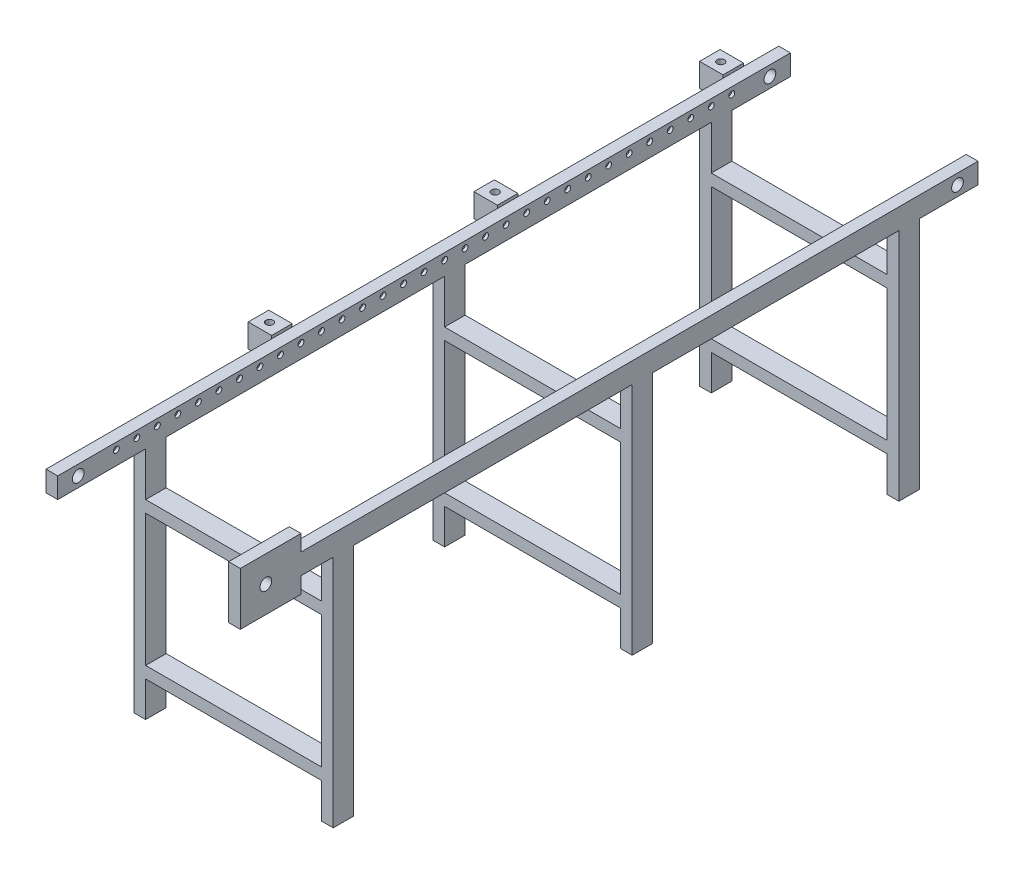
SolidWorks part; units mm, degrees
ref_plane "Front Plane" through (0, 0, 0) normal (0, 0, 1) x (1, 0, 0)
ref_plane "Top Plane" through (0, 0, 0) normal (0, 1, 0) x (1, 0, 0)
ref_plane "Right Plane" through (0, 0, 0) normal (1, 0, 0) x (0, 0, -1)
ref_plane "Plane1" through (300, 0, 0) normal (1, 0, 0) x (0, 0, -1)
sketch "Sketch3" plane through (300, 0, 0) normal (1, 0, 0) x (0, 0, -1)
  line L1 (-1250, 35) -> (1250, 35)
  line L2 (-1250, 35) -> (-1250, -35)
  line L3 (-1250, -35) -> (1250, -35)
  line L4 (1250, 35) -> (1250, -35)
  line L5 (-1250, 35) -> (1250, -35) construction
  line L6 (-1250, -35) -> (1250, 35) construction
  line L7 (-950, -35) -> (-880, -35)
  line L8 (-950, -35) -> (-950, -835)
  line L9 (-950, -835) -> (-880, -835)
  line L10 (-880, -35) -> (-880, -835)
  line L11 (70, -35) -> (140, -35)
  line L12 (70, -35) -> (70, -835)
  line L13 (70, -835) -> (140, -835)
  line L14 (140, -35) -> (140, -835)
  line L15 (980, -35) -> (1050, -35)
  line L16 (980, -35) -> (980, -835)
  line L17 (980, -835) -> (1050, -835)
  line L18 (1050, -35) -> (1050, -835)
  point P0 (0, 0)
  dimension "D1" = 2500
  dimension "D2" = 70
  dimension "D3" = 70
  dimension "D4" = 800
  dimension "D5" = 300
  dimension "D6" = 200
  dimension "D7" = 950
extrude "Boss-Extrude1" add sketch "Sketch3" along normal blind 40 contours L14 L3 L12 L13 | L4 L1 L2 L3 | L10 L3 L8 L9 | L18 L3 L16 L17
sketch "Sketch4" plane through (300, 0, 0) normal (-1, 0, 0) x (0, 0, 1)
  line L0 (-1050, -35) -> (-1050, -835) construction
  line L1 (-1050, -185) -> (-980, -185)
  line L2 (-1050, -185) -> (-1050, -225)
  line L3 (-1050, -225) -> (-980, -225)
  line L4 (-980, -185) -> (-980, -225)
  line L5 (-980, -35) -> (-980, -835) construction
  line L6 (-140, -35) -> (-140, -835) construction
  line L7 (-140, -185) -> (-70, -185)
  line L8 (-140, -185) -> (-140, -225)
  line L9 (-140, -225) -> (-70, -225)
  line L10 (-70, -185) -> (-70, -225)
  line L11 (-70, -35) -> (-70, -835) construction
  line L12 (880, -35) -> (880, -835) construction
  line L13 (880, -185) -> (950, -185)
  line L14 (880, -185) -> (880, -225)
  line L15 (880, -225) -> (950, -225)
  line L16 (950, -185) -> (950, -225)
  line L17 (950, -35) -> (950, -835) construction
  line L18 (-140, -35) -> (-980, -35) construction
  line L19 (-1050, -675) -> (-980, -675)
  line L20 (-1050, -675) -> (-1050, -715)
  line L21 (-1050, -715) -> (-980, -715)
  line L22 (-980, -675) -> (-980, -715)
  line L23 (-140, -675) -> (-70, -675)
  line L24 (-140, -675) -> (-140, -715)
  line L25 (-140, -715) -> (-70, -715)
  line L26 (-70, -675) -> (-70, -715)
  line L27 (880, -675) -> (950, -675)
  line L28 (880, -675) -> (880, -715)
  line L29 (880, -715) -> (950, -715)
  line L30 (950, -675) -> (950, -715)
  line L31 (-980, -835) -> (-1050, -835) construction
  dimension "D1" = 40
  dimension "D2" = 150
  dimension "D3" = 120
extrude "Boss-Extrude2" add sketch "Sketch4" along normal blind 300
mirror "Mirror2" about plane through (0, 0, 0) normal (1, 0, 0) of "Boss-Extrude1", "Boss-Extrude2"
mirror "Mirror3" about plane through (0, 0, 0) normal (1, 0, 0) of "Boss-Extrude1"
sketch "Sketch5" plane through (-300, 0, 0) normal (1, 0, 0) x (0, 0, -1)
  line L0 (-1250, 35) -> (1250, 35) construction
  line L1 (-1250, 35) -> (-1250, -35) construction
  circle A0 centre (-1050, 12.5) radius 10
  circle A1 centre (-980, 12.5) radius 10
  circle A2 centre (-910, 12.5) radius 10
  circle A3 centre (-840, 12.5) radius 10
  circle A4 centre (-770, 12.5) radius 10
  circle A5 centre (-700, 12.5) radius 10
  circle A6 centre (-630, 12.5) radius 10
  circle A7 centre (-560, 12.5) radius 10
  circle A8 centre (-490, 12.5) radius 10
  circle A9 centre (-420, 12.5) radius 10
  circle A10 centre (-350, 12.5) radius 10
  circle A11 centre (-280, 12.5) radius 10
  circle A12 centre (-210, 12.5) radius 10
  circle A13 centre (-140, 12.5) radius 10
  circle A14 centre (-70, 12.5) radius 10
  circle A15 centre (0, 12.5) radius 10
  circle A16 centre (70, 12.5) radius 10
  circle A17 centre (140, 12.5) radius 10
  circle A18 centre (210, 12.5) radius 10
  circle A19 centre (280, 12.5) radius 10
  circle A20 centre (350, 12.5) radius 10
  circle A21 centre (420, 12.5) radius 10
  circle A22 centre (490, 12.5) radius 10
  circle A23 centre (560, 12.5) radius 10
  circle A24 centre (630, 12.5) radius 10
  circle A25 centre (700, 12.5) radius 10
  circle A26 centre (770, 12.5) radius 10
  circle A27 centre (840, 12.5) radius 10
  circle A28 centre (910, 12.5) radius 10
  circle A29 centre (980, 12.5) radius 10
  circle A30 centre (1050, 12.5) radius 10
  dimension "D1" = 20
  dimension "D3" = 200
  dimension "D2" = 22.5
  dimension "D5" = 70
  dimension "D4" = 31
extrude "Cut-Extrude1" cut sketch "Sketch5" against normal blind 10
mirror "Mirror4" about plane through (0, 0, 0) normal (1, 0, 0) of "Cut-Extrude1"
sketch "Sketch6" plane through (-300, 0, 0) normal (1, 0, 0) x (0, 0, -1)
  line L0 (-1250, 35) -> (1250, 35) construction
  line L1 (-1250, 35) -> (-1250, -35) construction
  circle A0 centre (-1180, 0) radius 20
  dimension "D1" = 40
  dimension "D2" = 35
  dimension "D3" = 70
extrude "Cut-Extrude2" cut sketch "Sketch6" against normal through all both and the other way through all
sketch "Sketch7" plane through (0, -835, 0) normal (0, -1, 0) x (1, 0, 0)
  line L0 (340, 950) -> (300, 950) construction
  line L1 (300, 880) -> (300, 950) construction
  line L2 (-340, -980) -> (-300, -980) construction
  line L3 (-300, -980) -> (-300, -1050) construction
  line L4 (-340, -70) -> (-340, -140) construction
  line L5 (-340, -70) -> (-300, -70) construction
  line L7 (-300, 880) -> (-300, 950) construction
  circle A0 centre (320, 915) radius 7.5
  circle A1 centre (-320, 915) radius 7.5
  circle A2 centre (-320, -105) radius 7.5
  circle A3 centre (320, -105) radius 7.5
  circle A4 centre (-320, -105) radius 7.5
  circle A5 centre (-320, -1015) radius 7.5
  circle A6 centre (320, -1015) radius 7.5
  dimension "D1" = 15
  dimension "D2" = 35
  dimension "D3" = 20
  dimension "D11" = 35
  dimension "D12" = 2
  dimension "D13" = 20
  dimension "D7" = 35
  dimension "D8" = 20
  dimension "D9" = 640
  dimension "D10" = 20
  dimension "D4" = 2
  dimension "D5" = 2
  dimension "D6" = 2
extrude "Cut-Extrude3" cut sketch "Sketch7" against normal blind 20 contours A1 | A0 | A3 | A2 | A6 | A5
mirror "Mirror5" about plane through (0, 0, 0) normal (0, 0, 1) of "Cut-Extrude2"
sketch "Sketch8" plane through (-340, 0, 0) normal (-1, 0, 0) x (0, 0, 1)
  line L1 (-360, 45) -> (-290, 45)
  line L2 (-360, 45) -> (-360, -35)
  line L3 (-360, -35) -> (-290, -35)
  line L4 (-290, 45) -> (-290, -35)
  line L5 (410, -35) -> (480, -35)
  line L6 (410, -35) -> (410, 45)
  line L7 (410, 45) -> (480, 45)
  line L8 (480, -35) -> (480, 45)
  line L9 (-1130, -35) -> (-1060, -35)
  line L10 (-1130, -35) -> (-1130, 45)
  line L11 (-1130, 45) -> (-1060, 45)
  line L12 (-1060, -35) -> (-1060, 45)
  line L15 (-140, -35) -> (-980, -35) construction
  line L16 (880, -35) -> (-70, -35) construction
  line L18 (-1250, 35) -> (-1250, -35) construction
  point P15 (-976.325, 73.0291)
  point P16 (-978.7825, -35)
  point P19 (0, 0)
  point P20 (-292.0056, -35)
  point P22 (0, 0)
  point P23 (569.0513, -35)
  dimension "D1" = 700
  dimension "D2" = 700
  dimension "D3" = 80
  dimension "D4" = 70
  dimension "D5" = 120
extrude "Boss-Extrude3" add sketch "Sketch8" along normal blind 80
sketch "Sketch10" plane through (0, 45, 0) normal (0, 1, 0) x (1, 0, 0)
  line L0 (-420, 1130) -> (-340, 1130) construction
  line L1 (-420, 1060) -> (-420, 1130) construction
  line L3 (-420, 360) -> (-340, 360) construction
  line L4 (-420, -410) -> (-340, -410) construction
  circle A0 centre (-382.5008, 1095) radius 12.5
  circle A1 centre (-382.5008, 325) radius 12.5
  circle A2 centre (-382.5008, -445) radius 12.5
  point P10 (0, 0)
  point P13 (-382.5008, 370.5095)
  dimension "D1" = 25
  dimension "D2" = 35
  dimension "D3" = 37.4992
  dimension "D4" = 35
  dimension "D5" = 35
extrude "Cut-Extrude4" cut sketch "Sketch10" against normal blind 60
sketch "Sketch11" plane through (340, 0, 0) normal (1, 0, 0) x (0, 0, -1)
  line L1 (-1300, 90) -> (-1060, 90)
  line L2 (-1300, 90) -> (-1300, -90)
  line L3 (-1300, -90) -> (-1060, -90)
  line L4 (-1060, 90) -> (-1060, -90)
  line L5 (-1300, 90) -> (-1060, -90) construction
  line L6 (-1300, -90) -> (-1060, 90) construction
  circle A0 centre (-1180, 0) radius 20 construction
  circle A1 centre (-1180, 0) radius 20
  point P0 (-1180, 0)
  dimension "D1" = 180
  dimension "D2" = 240
extrude "Boss-Extrude4" add sketch "Sketch11" against normal up to surface (40 mm away) up to face at (300, -775, 915)
sketch "Sketch12" plane through (340, 0, 0) normal (1, 0, 0) x (0, 0, -1)
  line L0 (-1300, -90) -> (-1060, -90) construction
  line L1 (-1300, 90) -> (-1267, 90)
  line L2 (-1300, 90) -> (-1300, -90)
  line L3 (-1300, -90) -> (-1267, -90)
  line L4 (-1267, 90) -> (-1267, -90)
  dimension "D1" = 33
extrude "Cut-Extrude5" cut sketch "Sketch12" against normal through all
